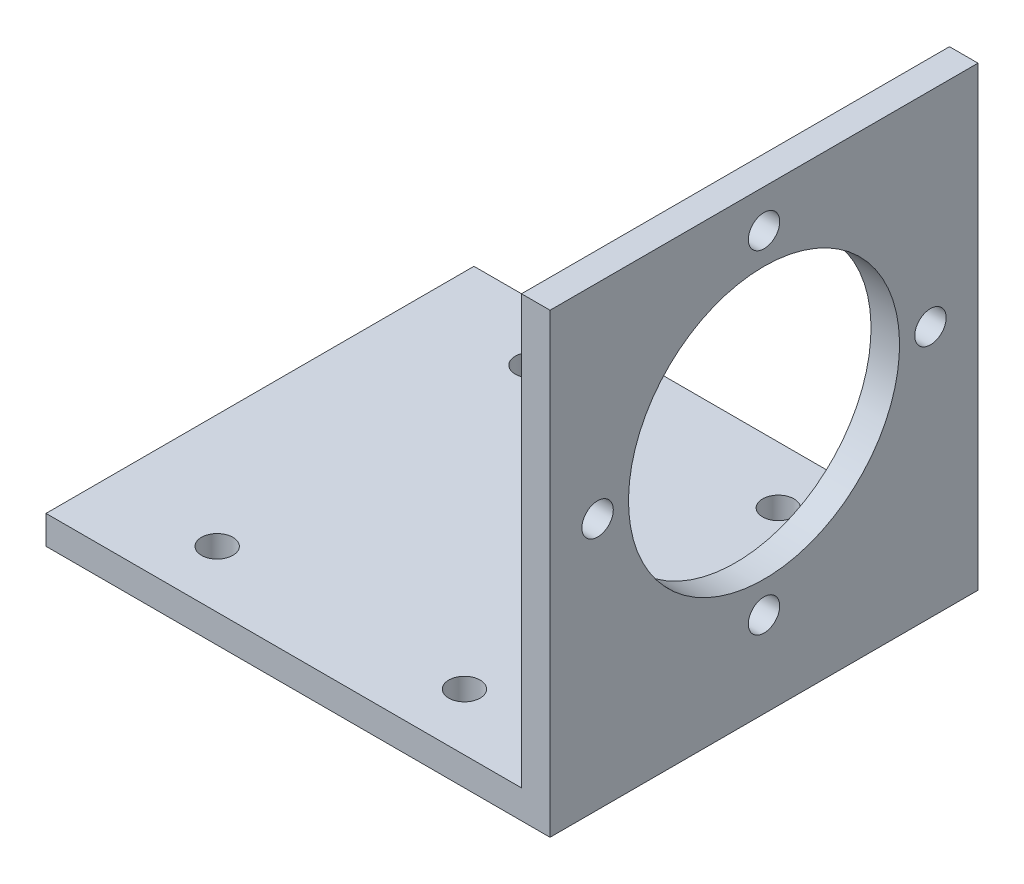
SolidWorks part; units mm, degrees
material "1060 Alloy"
ref_plane "Front Plane" through (0, 0, 0) normal (0, 0, 1) x (1, 0, 0)
ref_plane "Top Plane" through (0, 0, 0) normal (0, 1, 0) x (1, 0, 0)
ref_plane "Right Plane" through (0, 0, 0) normal (1, 0, 0) x (0, 0, -1)
sketch "Sketch1" plane through (0, 0, 0) normal (0, 0, 1) x (1, 0, 0)
  line L0 (0, 0) -> (53, 0)
  line L1 (53, 0) -> (53, 48)
  line L2 (53, 48) -> (50, 48)
  line L3 (50, 48) -> (50, 3)
  line L4 (50, 3) -> (0, 3)
  line L5 (0, 3) -> (0, 0)
  dimension "D1" = 3
  dimension "D2" = 3
  dimension "D3" = 45
  dimension "D4" = 50
extrude "Boss-Extrude1" add sketch "Sketch1" along normal blind 45
sketch "Sketch7" plane through (53, 0, 0) normal (1, 0, 0) x (0, 0, -1)
  line L0 (0, 0) -> (0, 48) construction
  line L1 (-4, 40) -> (-2, 40)
  line L2 (-4, 40) -> (-4, 30)
  line L3 (-4, 30) -> (-2, 30)
  line L4 (-2, 40) -> (-2, 30)
  line L5 (-45, 48) -> (0, 48) construction
  line L6 (-4, 16) -> (-2, 16)
  line L7 (-4, 16) -> (-4, 6)
  line L8 (-4, 6) -> (-2, 6)
  line L9 (-2, 16) -> (-2, 6)
  point P6 (-3, 40)
  dimension "D1" = 2
  dimension "D2" = 8
  dimension "D3" = 2
  dimension "D4" = 10
  dimension "D5" = 2
extrude "Cut-Extrude3" [suppressed] cut sketch "Sketch7" against normal up to surface (3 mm away)
sketch "Sketch8" plane through (0, 3, 0) normal (0, 1, 0) x (1, 0, 0)
  line L0 (50, -45) -> (50, 0) construction
  line L1 (50, 0) -> (0, 0) construction
  line L2 (0, -45) -> (0, 0) construction
  line L3 (50, -22.5) -> (0, -22.5) construction
  circle A0 centre (38, -6) radius 2
  circle A1 centre (12, -6) radius 2
  circle A2 centre (12, -39) radius 2
  circle A3 centre (38, -39) radius 2
  dimension "D3" = 4
  dimension "D4" = 4
  dimension "D1" = 12
  dimension "D2" = 6
  dimension "D5" = 12
  dimension "D6" = 6
extrude "Cut-Extrude4" [suppressed] cut sketch "Sketch8" against normal up to surface (3 mm away)
sketch "Sketch9" plane through (53, 0, 0) normal (1, 0, 0) x (0, 0, -1)
  line L2 (0, 0) -> (0, 48) construction
  line L3 (-45, 0) -> (0, 0) construction
  point P0 (-22.5, 44)
  point P1 (-5, 26.5)
  point P2 (0, 0)
  point P3 (-40, 26.5)
  point P4 (0, 0)
  point P5 (-22.5, 9)
  point P6 (0, 0)
  point P7 (0, 0)
  point P8 (0, 0)
  point P9 (0, 0)
  point P10 (0, 0)
  point P11 (0, 0)
  point P19 (-22.5, 0)
  dimension "D3" = 5
  dimension "D5" = 9
  dimension "D1" = 35
  dimension "D2" = 17.5
  dimension "D8" = 35
  dimension "D7" = 17.5
  dimension "D6" = 17.5
sketch "Sketch12" plane through (0, 3, 0) normal (0, 1, 0) x (1, 0, 0)
  line L0 (50, -45) -> (0, -45) construction
  line L1 (50, -45) -> (50, 0) construction
  line L2 (0, -45) -> (0, 0) construction
  line L3 (50, 0) -> (0, 0) construction
  point P0 (38, -39)
  point P1 (12, -39)
  point P3 (12, -6)
  point P5 (38, -6)
  dimension "D1" = 6
  dimension "D2" = 12
  dimension "D3" = 6
  dimension "D4" = 12
  dimension "D5" = 6
  dimension "D6" = 12
  dimension "D7" = 6
  dimension "D8" = 12
hole_wizard "M4 Tapped Hole12" positions "Sketch13" profile "Sketch14" tap size "M4" standard "ISO"
sketch "Sketch13" plane through (0, 3, 0) normal (0, 1, 0) x (1, 0, 0)
  point P0 (38, -39)
  point P3 (12, -39)
  point P6 (12, -6)
  point P9 (38, -6)
sketch "Sketch14" plane through (38, 3, 39) normal (1, 0, 0) x (0, 0, 1)
  line L0 (0, 0) -> (0, 3.9904)
  line L1 (0, 3.9904) -> (1.65, 2.999)
  line L2 (1.65, 2.999) -> (1.65, 0)
  line L5 (1.65, 0) -> (0, 0)
  line L10 (0, 3.9904) -> (-1.65, 2.999) construction
  line L11 (0, -6.35) -> (0, 107.95) construction
  dimension "Tap Drill Dia." = 3.3
  dimension "Tap Drill Depth" = 2.999
  dimension "Drill Angle" = 118
cosmetic thread "Hole Thread6" parameters "D1"=3, "D2"=4
cosmetic thread "Hole Thread7" parameters "D1"=3, "D2"=4
cosmetic thread "Hole Thread8" parameters "D1"=3, "D2"=4
cosmetic thread "Hole Thread9" parameters "D1"=3, "D2"=4
hole_wizard "M4 Tapped Hole13" positions "Sketch21" profile "Sketch22" tap size "M4" standard "ISO"
sketch "Sketch21" plane through (53, 0, 0) normal (1, 0, 0) x (0, 0, -1)
  point P0 (-22.5, 44)
  point P3 (-5, 26.5)
  point P6 (-22.5, 9)
  point P9 (-40, 26.5)
sketch "Sketch22" plane through (53, 44, 22.5) normal (0, 1, 0) x (0, 0, -1)
  line L0 (0, 0) -> (0, 3.9904)
  line L1 (0, 3.9904) -> (1.65, 2.999)
  line L2 (1.65, 2.999) -> (1.65, 0)
  line L5 (1.65, 0) -> (0, 0)
  line L10 (0, 3.9904) -> (-1.65, 2.999) construction
  line L11 (0, -6.35) -> (0, 107.95) construction
  dimension "Tap Drill Dia." = 3.3
  dimension "Tap Drill Depth" = 2.999
  dimension "Drill Angle" = 118
cosmetic thread "Hole Thread10" parameters "D1"=3, "D2"=4
cosmetic thread "Hole Thread11" parameters "D1"=3, "D2"=4
cosmetic thread "Hole Thread12" parameters "D1"=3, "D2"=4
cosmetic thread "Hole Thread13" parameters "D1"=3, "D2"=4
sketch "Sketch23" plane through (53, 0, 0) normal (1, 0, 0) x (0, 0, -1)
  line L0 (-40, 26.5) -> (-5, 26.5) construction
  circle A0 centre (-22.5, 26.5) radius 14.25
  point P6 (0, 0)
  dimension "D1" = 28.5
extrude "Cut-Extrude5" cut sketch "Sketch23" against normal up to surface (3 mm away) up to face at (50, 45.65, 22.5)
equation "\"D2@Sketch1\"=\"D1@Sketch1\""
equation "\"housingWidth\"=48"
equation "\"housingThickness\"= 3"
equation "\"D1@Sketch1\"=\"housingThickness\""
equation "\"housingLength\"=50"
equation "\"D4@Sketch1\"=\"housingLength\""
equation "\"D6@Sketch8\"=\"D2@Sketch8\""
equation "\"D5@Sketch8\"=\"D1@Sketch8\""
equation "\"bracketWidth\"=45"
equation "\"D3@Sketch9\"=(\"bracketWidth\"-35)/2"
equation "\"D1@Boss-Extrude1\"=\"bracketWidth\""
